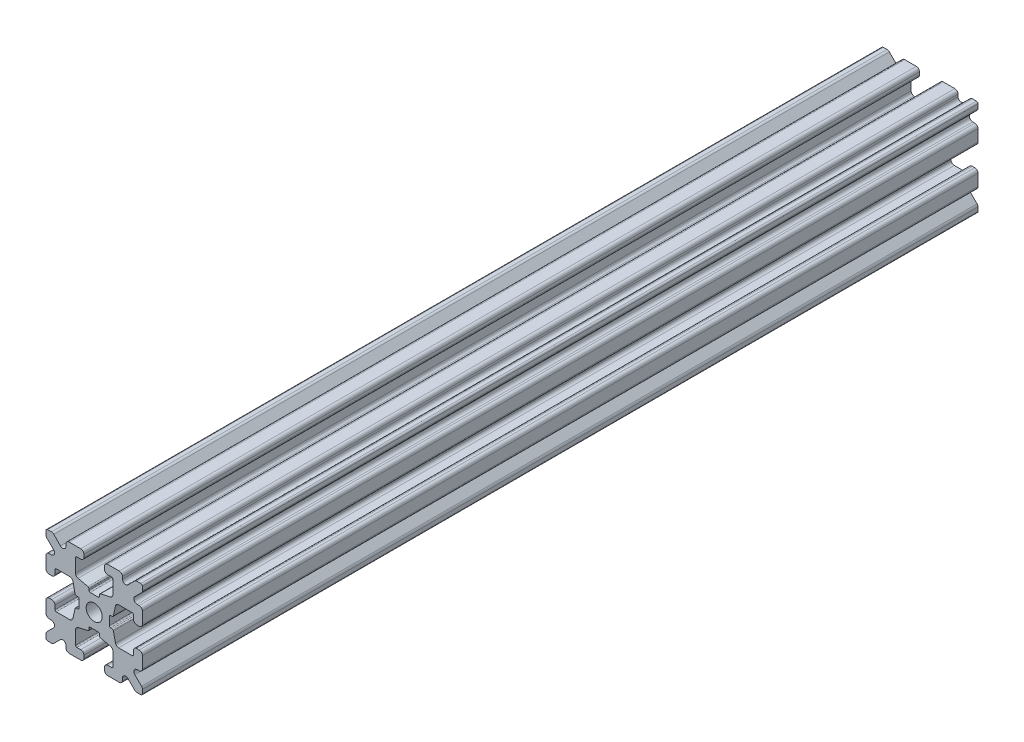
SolidWorks part; units mm, degrees
ref_plane "Front Plane" through (0, 0, 0) normal (0, 0, 1) x (1, 0, 0)
ref_plane "Top Plane" through (0, 0, 0) normal (0, 1, 0) x (1, 0, 0)
ref_plane "Right Plane" through (0, 0, 0) normal (1, 0, 0) x (0, 0, -1)
sketch "Sketch1" plane through (0, 0, 0) normal (0, 0, 1) x (1, 0, 0)
  line L1 (-7.5, -7.5) -> (7.5, -7.5)
  line L2 (-7.5, -7.5) -> (-7.5, 7.5)
  line L3 (-7.5, 7.5) -> (7.5, 7.5)
  line L4 (7.5, -7.5) -> (7.5, 7.5)
  line L5 (-7.5, -7.5) -> (7.5, 7.5) construction
  line L6 (-7.5, 7.5) -> (7.5, -7.5) construction
  circle A0 centre (0, 0) radius 1.25
  point P0 (0, 0)
  dimension "D2" = 2.5
  dimension "D1" = 15
extrude "Boss-Extrude1" add sketch "Sketch1" along normal mid plane 130
fillet "Fillet1" radius 0.25 4 edges at (7.5, -7.5, 0) (-7.5, -7.5, 0) (7.5, 7.5, 0) (-7.5, 7.5, 0)
sketch "Sketch2" plane through (0, 0, 65) normal (0, 0, 1) x (1, 0, 0)
  line L0 (-7.5, 7.25) -> (-7.5, -7.25) construction
  line L1 (-7.5, 1.6) -> (-6.1, 1.6)
  line L2 (-7.5, 1.6) -> (-7.5, -1.6)
  line L3 (-7.5, -1.6) -> (-6.1, -1.6)
  line L4 (-6.1, 1.6) -> (-6.1, 2.9)
  line L5 (0, 0) -> (-12.1036, 0) construction
  line L6 (-6.1, -2.9) -> (-3.4, -2.9)
  line L7 (0, 0) -> (-7.25, 7.25) construction
  line L8 (-6.1, 2.9) -> (-3.4, 2.9)
  line L9 (-3.4, -2.9) -> (-3.4, 2.9)
  line L10 (55, 0) -> (-55, 0) construction
  line L11 (-6.1, -2.9) -> (-6.1, -1.6)
  line L12 (2.9, 6.1) -> (1.6, 6.1)
  line L13 (2.9, 3.4) -> (-2.9, 3.4)
  line L14 (-2.9, 6.1) -> (-2.9, 3.4)
  line L15 (2.9, 6.1) -> (2.9, 3.4)
  line L16 (-1.6, 6.1) -> (-2.9, 6.1)
  line L17 (1.6, 7.5) -> (1.6, 6.1)
  line L18 (-1.6, 7.5) -> (1.6, 7.5)
  line L19 (-1.6, 7.5) -> (-1.6, 6.1)
  line L20 (-1.6, -7.5) -> (-1.6, -6.1)
  line L21 (-1.6, -7.5) -> (1.6, -7.5)
  line L22 (1.6, -7.5) -> (1.6, -6.1)
  line L23 (-1.6, -6.1) -> (-2.9, -6.1)
  line L24 (2.9, -6.1) -> (2.9, -3.4)
  line L25 (-2.9, -6.1) -> (-2.9, -3.4)
  line L26 (2.9, -3.4) -> (-2.9, -3.4)
  line L27 (2.9, -6.1) -> (1.6, -6.1)
  line L28 (6.1, -2.9) -> (6.1, -1.6)
  line L29 (3.4, -2.9) -> (3.4, 2.9)
  line L30 (6.1, 2.9) -> (3.4, 2.9)
  line L31 (6.1, -2.9) -> (3.4, -2.9)
  line L32 (6.1, 1.6) -> (6.1, 2.9)
  line L33 (7.5, -1.6) -> (6.1, -1.6)
  line L34 (7.5, 1.6) -> (7.5, -1.6)
  line L35 (7.5, 1.6) -> (6.1, 1.6)
  dimension "D1" = 3.2
  dimension "D2" = 5.8
  dimension "D3" = 1.4
  dimension "D4" = 2.7
extrude "Cut-Extrude1" cut sketch "Sketch2" against normal through all
sketch "Sketch4" plane through (0, 0, 65) normal (0, 0, 1) x (1, 0, 0)
  line L0 (-3.4, 2.9) -> (-2.75, 0)
  line L1 (55, 0) -> (-55, 0) construction
  line L2 (-2.75, 0) -> (-3.4, -2.9)
  line L3 (-3.4, -2.9) -> (-3.4, 2.9) construction
  line L4 (-3.4, 2.9) -> (-3.4, -2.9)
  line L5 (-2.9, 3.4) -> (0, 2.75)
  line L6 (0, 2.75) -> (2.9, 3.4)
  line L7 (2.9, 3.4) -> (-2.9, 3.4)
  line L8 (3.4, 2.9) -> (2.75, 0)
  line L9 (2.75, 0) -> (3.4, -2.9)
  line L10 (3.4, -2.9) -> (3.4, 2.9)
  line L11 (-2.9, -3.4) -> (0, -2.75)
  line L12 (0, -2.75) -> (2.9, -3.4)
  line L13 (2.9, -3.4) -> (-2.9, -3.4)
  circle A2 centre (0, 0) radius 2.75
  circle A3 centre (0, 0) radius 2.75 construction
  dimension "D1" = 1.5
extrude "Cut-Extrude3" cut sketch "Sketch4" against normal through all
fillet "Fillet3" radius 0.5 16 edges at (-6.1, -1.6, 0) (-7.5, -1.6, 0) (-6.1, 1.6, 0) (-7.5, 1.6, 0) (-1.6, -7.5, 0) (-1.6, -6.1, 0) (1.6, -7.5, 0) (1.6, -6.1, 0) (6.1, -1.6, 0) (7.5, -1.6, 0) (7.5, 1.6, 0) (6.1, 1.6, 0) (1.6, 7.5, 0) (1.6, 6.1, 0) (-1.6, 7.5, 0) (-1.6, 6.1, 0)
fillet "Fillet4" radius 0.5 8 edges at (-3.4, 2.9, 0) (-3.4, -2.9, 0) (2.9, -3.4, 0) (-2.9, -3.4, 0) (3.4, -2.9, 0) (3.4, 2.9, 0) (-2.9, 3.4, 0) (2.9, 3.4, 0)
fillet "Fillet5" radius 3 4 edges at (0, -2.75, 0) (2.75, 0, 0) (-2.75, 0, 0) (0, 2.75, 0)
fillet "Fillet6" radius 0.2 8 edges at (-2.9, -6.1, 0) (2.9, -6.1, 0) (6.1, -2.9, 0) (6.1, 2.9, 0) (2.9, 6.1, 0) (-2.9, 6.1, 0) (-6.1, -2.9, 0) (-6.1, 2.9, 0)
sketch "Sketch5" plane through (0, 0, 65) normal (0, 0, 1) x (1, 0, 0)
  line L0 (0, 0) -> (-7.25, 7.25) construction
  line L1 (-7.5, 6.4393) -> (-5.4607, 4.4)
  line L2 (-6.4393, 7.5) -> (-4.4, 5.4607)
  line L3 (-7.5, 4.4) -> (-5.4607, 4.4)
  line L4 (-3.8003, 2.9) -> (-5.9, 2.9) construction
  line L5 (0, 0) -> (-12.1819, 0) construction
  line L6 (-4.4, 7.5) -> (-4.4, 5.4607)
  line L7 (-2.9, 5.9) -> (-2.9, 3.8003) construction
  line L8 (-7.5, 6.4393) -> (-7.5, 4.4)
  line L9 (-7.5, 7.25) -> (-7.5, 2.1) construction
  line L10 (2.1, -7.5) -> (7.25, -7.5) construction
  line L11 (7.5, -7.25) -> (7.5, -2.1) construction
  line L12 (7.25, 7.5) -> (2.1, 7.5) construction
  line L13 (-2.1, 7.5) -> (-7.25, 7.5) construction
  line L14 (-4.4, 7.5) -> (-6.4393, 7.5)
  line L16 (55, 0) -> (-55, 0) construction
  line L17 (0, 0) -> (0, 10.993) construction
  line L18 (0, -54.6431) -> (0, 54.6431) construction
  line L20 (4.4, 7.5) -> (6.4393, 7.5)
  line L22 (7.5, 6.4393) -> (7.5, 4.4)
  line L23 (4.4, 7.5) -> (4.4, 5.4607)
  line L24 (7.5, 4.4) -> (5.4607, 4.4)
  line L25 (6.4393, 7.5) -> (4.4, 5.4607)
  line L26 (7.5, 6.4393) -> (5.4607, 4.4)
  line L27 (7.5, -6.4393) -> (5.4607, -4.4)
  line L28 (6.4393, -7.5) -> (4.4, -5.4607)
  line L29 (7.5, -4.4) -> (5.4607, -4.4)
  line L30 (4.4, -7.5) -> (4.4, -5.4607)
  line L31 (7.5, -6.4393) -> (7.5, -4.4)
  line L33 (4.4, -7.5) -> (6.4393, -7.5)
  line L36 (-4.4, -7.5) -> (-6.4393, -7.5)
  line L38 (-7.5, -6.4393) -> (-7.5, -4.4)
  line L39 (-4.4, -7.5) -> (-4.4, -5.4607)
  line L40 (-7.5, -4.4) -> (-5.4607, -4.4)
  line L41 (-6.4393, -7.5) -> (-4.4, -5.4607)
  line L42 (-7.5, -6.4393) -> (-5.4607, -4.4)
  dimension "D1" = 1.5
  dimension "D2" = 1.5
  dimension "D3" = 1.5
extrude "Cut-Extrude4" cut sketch "Sketch5" against normal through all
fillet "Fillet8" radius 0.5 24 edges at (-5.4607, 4.4, 0) (-7.5, 4.4, 0) (-5.4607, -4.4, 0) (-7.5, -4.4, 0) (-4.4, -7.5, 0) (-4.4, -5.4607, 0) (4.4, -7.5, 0) (4.4, -5.4607, 0) (5.4607, -4.4, 0) (7.5, -4.4, 0) (7.5, 4.4, 0) (5.4607, 4.4, 0) (4.4, 5.4607, 0) (4.4, 7.5, 0) (-4.4, 5.4607, 0) (-4.4, 7.5, 0) (-6.4393, 7.5, 0) (-7.5, 6.4393, 0) (6.4393, 7.5, 0) (7.5, 6.4393, 0) (6.4393, -7.5, 0) (7.5, -6.4393, 0) (-6.4393, -7.5, 0) (-7.5, -6.4393, 0)
sketch "Sketch6" plane through (0, 0, 65) normal (0, 0, 1) x (1, 0, 0)
  line L0 (0, 0) -> (0, 11.013) construction
  line L1 (0.6561, 2.8971) -> (2.1235, 2.8971) construction
  line L2 (0, -54.6431) -> (0, 54.6431) construction
  line L3 (0, 0) -> (7.25, 7.25) construction
  line L4 (7.5, 0.8255) -> (7.5, -0.8255)
  line L5 (2.3471, 0.8255) -> (7.5, 0.8255)
  line L6 (0, 0) -> (12.4016, 0) construction
  line L7 (0.8255, -7.5) -> (-0.8255, -7.5)
  line L8 (2.3471, -0.8255) -> (2.3471, 0.8255)
  line L9 (0.8255, -2.3471) -> (0.8255, -7.5)
  line L10 (7.5, -0.8255) -> (2.3471, -0.8255)
  line L11 (-7.5, -0.8255) -> (-2.3471, -0.8255)
  line L12 (-2.3471, -0.8255) -> (-2.3471, 0.8255)
  line L13 (-0.8255, -2.3471) -> (0.8255, -2.3471)
  line L14 (-0.8255, 7.5) -> (-0.8255, 2.3471)
  line L15 (-0.8255, 2.3471) -> (0.8255, 2.3471)
  line L16 (-0.8255, -7.5) -> (-0.8255, -2.3471)
  line L17 (0.8255, 2.3471) -> (0.8255, 7.5)
  line L18 (0.8255, 7.5) -> (-0.8255, 7.5)
  line L19 (3.9, 7.5) -> (2.1, 7.5) construction
  line L20 (-2.3471, 0.8255) -> (-7.5, 0.8255)
  line L21 (-7.5, 0.8255) -> (-7.5, -0.8255)
  point P5 (0, -2.5973)
  point P7 (0, 2.5973)
  dimension "D3" = 0.55
  dimension "D1" = 1.651
extrude "Cut-Extrude5" cut sketch "Sketch6" against normal through all
fillet "Fillet10" radius 0.2 16 edges at (-2.935, 0.8255, 0) (-2.935, -0.8255, 0) (2.935, -0.8255, 0) (2.935, 0.8255, 0) (0.8255, 2.935, 0) (-0.8255, 2.935, 0) (-2.3471, 0.8255, 0) (-2.3471, -0.8255, 0) (0.8255, 2.3471, 0) (-0.8255, 2.3471, 0) (2.3471, 0.8255, 0) (2.3471, -0.8255, 0) (0.8255, -2.935, 0) (0.8255, -2.3471, 0) (-0.8255, -2.3471, 0) (-0.8255, -2.935, 0)
